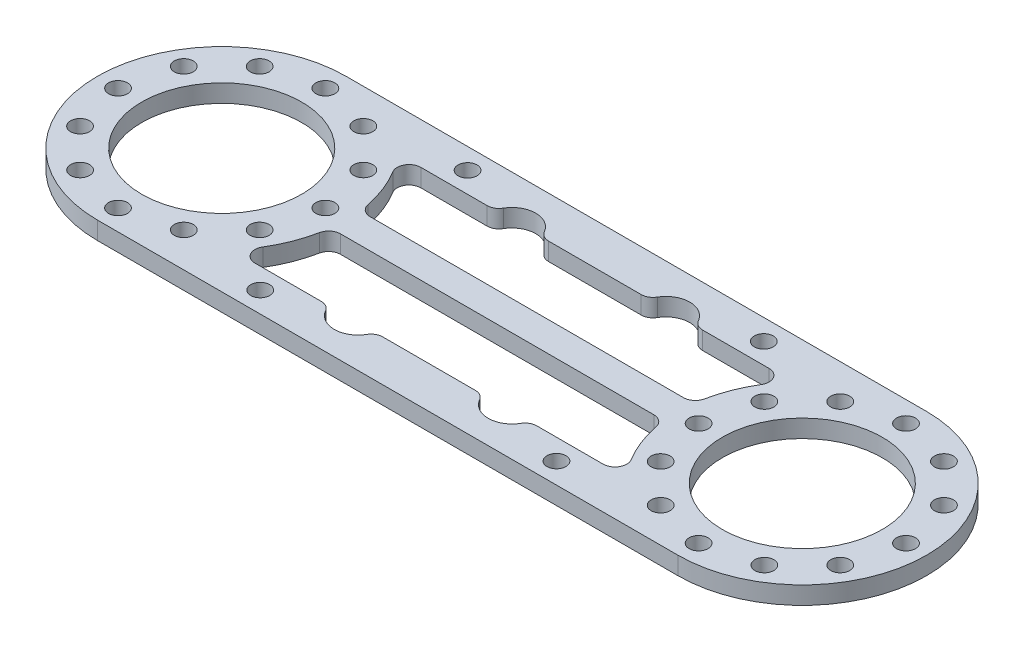
SolidWorks part; units mm, degrees
material "Thornel Mat VMA"
ref_plane "前视基准面" through (0, 0, 0) normal (0, 0, 1) x (1, 0, 0)
ref_plane "上视基准面" through (0, 0, 0) normal (0, 1, 0) x (1, 0, 0)
ref_plane "右视基准面" through (0, 0, 0) normal (1, 0, 0) x (0, 0, -1)
other "Configuration Table"
sketch "草图1" plane through (0, 0, 0) normal (0, 1, 0) x (1, 0, 0)
  line L0 (-50, 0) -> (50, 0) construction
  line L1 (-50, 21) -> (50, 21) construction
  line L2 (-50, -21) -> (50, -21) construction
  line L3 (0, -32.5) -> (0, 32.763) construction
  line L4 (-87.3644, -32.5) -> (86.7644, -32.5) construction
  line L5 (-49, -65) -> (49, -65) construction
  line L6 (-49, -44) -> (49, -44)
  line L7 (-49, -86) -> (49, -86)
  arc A0 (-50, 21) -> (-50, -21) centre (-50, 0) ccw construction
  arc A1 (50, -21) -> (50, 21) centre (50, 0) ccw construction
  circle A2 centre (-50, 0) radius 13.5 construction
  circle A3 centre (-50, 17.5) radius 1.6 construction
  circle A4 centre (-13, 13) radius 1.6 construction
  circle A5 centre (-13, -13) radius 1.6 construction
  circle A6 centre (-41.25, 15.1554) radius 1.6 construction
  circle A7 centre (-34.8446, 8.75) radius 1.6 construction
  circle A8 centre (-32.5, 0) radius 1.6 construction
  circle A9 centre (-34.8446, -8.75) radius 1.6 construction
  circle A10 centre (-41.25, -15.1554) radius 1.6 construction
  circle A11 centre (-50, -17.5) radius 1.6 construction
  circle A12 centre (-58.75, -15.1554) radius 1.6 construction
  circle A13 centre (-65.1554, -8.75) radius 1.6 construction
  circle A14 centre (-67.5, 0) radius 1.6 construction
  circle A15 centre (-65.1554, 8.75) radius 1.6 construction
  circle A16 centre (-58.75, 15.1554) radius 1.6 construction
  circle A17 centre (58.75, 15.1554) radius 1.6 construction
  circle A18 centre (65.1554, 8.75) radius 1.6 construction
  circle A19 centre (67.5, 0) radius 1.6 construction
  circle A20 centre (65.1554, -8.75) radius 1.6 construction
  circle A21 centre (58.75, -15.1554) radius 1.6 construction
  circle A22 centre (50, -17.5) radius 1.6 construction
  circle A23 centre (41.25, -15.1554) radius 1.6 construction
  circle A24 centre (34.8446, -8.75) radius 1.6 construction
  circle A25 centre (32.5, 0) radius 1.6 construction
  circle A26 centre (41.25, 15.1554) radius 1.6 construction
  circle A27 centre (13, -13) radius 1.6 construction
  circle A28 centre (13, 13) radius 1.6 construction
  circle A29 centre (50, 17.5) radius 1.6 construction
  circle A30 centre (50, 0) radius 13.5 construction
  circle A31 centre (34.8446, 8.75) radius 1.6 construction
  circle A32 centre (-49, -65) radius 13.5
  circle A33 centre (49, -65) radius 13.5
  arc A34 (-49, -44) -> (-49, -86) centre (-49, -65) ccw
  arc A35 (49, -86) -> (49, -44) centre (49, -65) ccw
  circle A36 centre (-49, -82.5) radius 1.6
  circle A37 centre (-57.75, -80.1554) radius 1.6
  circle A38 centre (-64.1554, -73.75) radius 1.6
  circle A39 centre (-66.5, -65) radius 1.6
  circle A40 centre (-64.1554, -56.25) radius 1.6
  circle A41 centre (-57.75, -49.8446) radius 1.6
  circle A42 centre (-49, -47.5) radius 1.6
  circle A43 centre (-40.25, -49.8446) radius 1.6
  circle A44 centre (-33.8446, -56.25) radius 1.6
  circle A45 centre (-31.5, -65) radius 1.6
  circle A46 centre (-33.8446, -73.75) radius 1.6
  circle A47 centre (-40.25, -80.1554) radius 1.6
  circle A48 centre (64.1554, -56.25) radius 1.6
  circle A49 centre (66.5, -65) radius 1.6
  circle A50 centre (64.1554, -73.75) radius 1.6
  circle A51 centre (57.75, -80.1554) radius 1.6
  circle A52 centre (49, -82.5) radius 1.6
  circle A53 centre (40.25, -80.1554) radius 1.6
  circle A54 centre (33.8446, -73.75) radius 1.6
  circle A55 centre (31.5, -65) radius 1.6
  circle A56 centre (33.8446, -56.25) radius 1.6
  circle A57 centre (40.25, -49.8446) radius 1.6
  circle A58 centre (49, -47.5) radius 1.6
  circle A59 centre (57.75, -49.8446) radius 1.6
  circle A60 centre (13, -52) radius 1.6
  circle A61 centre (-13, -52) radius 1.6
  circle A62 centre (13, -78) radius 1.6
  circle A63 centre (-13, -78) radius 1.6
  arc A64 (68.5201, -9.8999) -> (67.8158, -55.6745) centre (112.6154, -33.471) ccw construction
  arc A65 (-68.5201, -9.8999) -> (-67.8158, -55.6745) centre (-112.6154, -33.471) cw construction
  point P2 (0, 0)
  point P40 (-50, 0)
  point P67 (50, 0)
  point P78 (0, -65)
  point P113 (-49, -65)
  dimension "D2" = 21
  dimension "D3" = 27
  dimension "D5" = 3.2
  dimension "D9" = 3.2
  dimension "D13" = 100
  dimension "D1" = 100
  dimension "D4" = 17.5
  dimension "D6" = 26
  dimension "D7" = 13
  dimension "D8" = 13
  dimension "D11" = 32.5
  dimension "D14" = 98
  dimension "D15" = 17.5
  dimension "D10" = 12
  dimension "D12" = 12
extrude "凸台-拉伸1" add sketch "草图1" along normal blind 3
sketch "草图2" plane through (0, 3, 0) normal (0, 1, 0) x (1, 0, 0)
  line L0 (-49, -86) -> (49, -86) construction
  line L1 (-49, -51) -> (49, -51)
  line L2 (-49, -51) -> (-49, -79)
  line L3 (-49, -79) -> (49, -79)
  line L4 (49, -51) -> (49, -79)
  circle A0 centre (-49, -65) radius 21
  circle A1 centre (49, -65) radius 21
  circle A2 centre (13, -78) radius 4
  circle A3 centre (-13, -78) radius 4
  circle A4 centre (-13, -52) radius 4
  circle A5 centre (13, -52) radius 4
  point P12 (49, -65)
  circle M8 centre (-13, -52) radius 1.6
  circle M9 centre (13, -52) radius 1.6
  circle M40 centre (13, -78) radius 1.6
  circle M41 centre (-13, -78) radius 1.6
  dimension "D2" = 8
  dimension "D1" = 7
extrude "切除-拉伸1" cut sketch "草图2" against normal blind 10 contours A5 L1 A4 A0 L3 A3 A2 A1 | L3 A2 M40 | L3 A2 M40 | L1 A4 M8 | L1 A4 M8 | L1 A5 M9 | L1 A5 M9 | L3 A3 M41
sketch "草图3" plane through (0, 3, 0) normal (0, 1, 0) x (1, 0, 0)
  line L0 (-29.9, -65) -> (29.9, -65)
  circle A0 centre (-31.5, -65) radius 1.6 construction
  circle A1 centre (31.5, -65) radius 1.6 construction
extrude "拉伸-薄壁1" add sketch "草图3" against normal blind 3 thin thin type mid plane wall 5
fillet "圆角1" radius 2 16 edges at (-9.127, 1.5, 51) (-16.873, 1.5, 51) (-33.3475, 1.5, 51) (16.873, 1.5, 51) (9.127, 1.5, 51) (33.3475, 1.5, 51) (28.1493, 1.5, 62.5) (-28.1493, 1.5, 62.5) (28.1493, 1.5, 67.5) (33.3475, 1.5, 79) (9.127, 1.5, 79) (16.873, 1.5, 79) (-16.873, 1.5, 79) (-9.127, 1.5, 79) (-33.3475, 1.5, 79) (-28.1493, 1.5, 67.5)
sketch "草图4" plane through (0, 3, 0) normal (0, 1, 0) x (1, 0, 0)
  line L1 (-25, -47.5) -> (25, -47.5) construction
  line L2 (-25, -47.5) -> (-25, -82.5) construction
  line L3 (-25, -82.5) -> (25, -82.5) construction
  line L4 (25, -47.5) -> (25, -82.5) construction
  line L5 (-25, -47.5) -> (25, -82.5) construction
  line L6 (-25, -82.5) -> (25, -47.5) construction
  circle A0 centre (49, -82.5) radius 1.6 construction
  circle A1 centre (-49, -82.5) radius 1.6 construction
  circle A2 centre (-49, -47.5) radius 1.6 construction
  circle A3 centre (49, -47.5) radius 1.6 construction
  circle A4 centre (-49, -82.5) radius 1.6
  circle A5 centre (-49, -47.5) radius 1.6
  circle A6 centre (49, -47.5) radius 1.6 construction
  circle A7 centre (49, -82.5) radius 1.6 construction
  circle A8 centre (31.5, -65) radius 1.6 construction
  circle A9 centre (31.5, -65) radius 1.6 construction
  circle A10 centre (25, -82.5) radius 1.6
  circle A11 centre (-25, -82.5) radius 1.6
  circle A12 centre (-25, -47.5) radius 1.6
  circle A13 centre (25, -47.5) radius 1.6
  point P0 (0, -65)
  dimension "D1" = 50
extrude "切除-拉伸2" cut sketch "草图4" against normal blind 10
